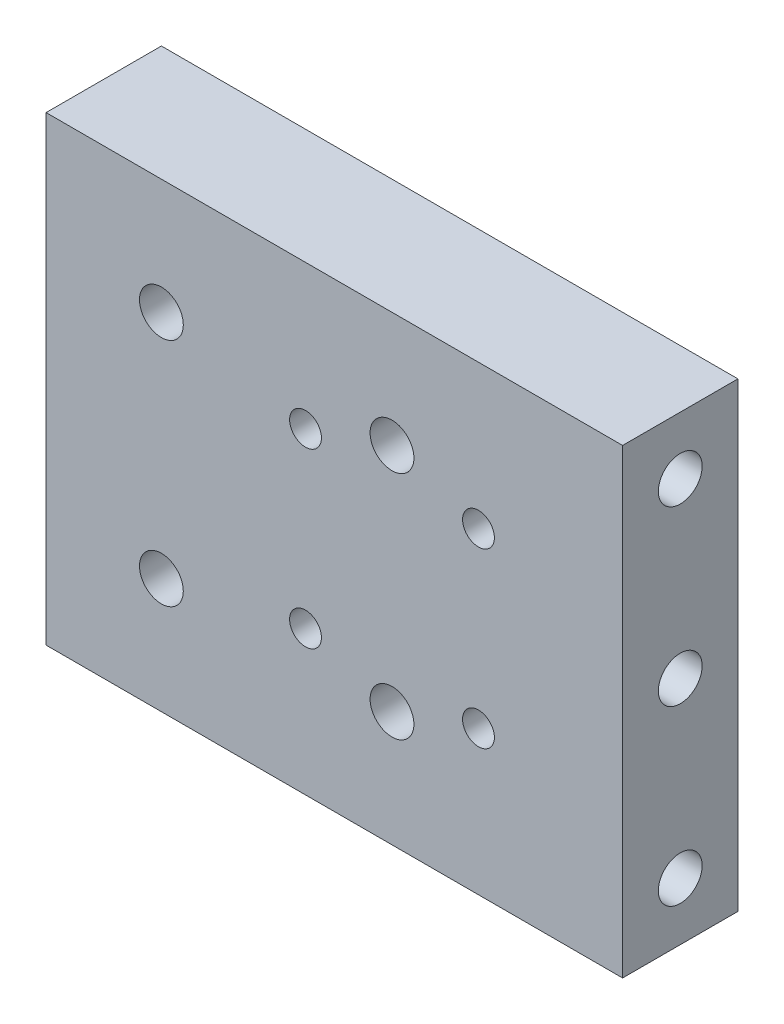
SolidWorks part; units mm, degrees
ref_plane "Front" through (0, 0, 0) normal (0, 0, 1) x (1, 0, 0)
ref_plane "Top" through (0, 0, 0) normal (0, 1, 0) x (1, 0, 0)
ref_plane "Right" through (0, 0, 0) normal (1, 0, 0) x (0, 0, -1)
sketch "Sketch1" plane through (0, 0, 0) normal (0, 0, 1) x (1, 0, 0)
  line L1 (0, 0) -> (-63.5, 0)
  line L2 (0, 0) -> (0, 50.8)
  line L3 (0, 50.8) -> (-63.5, 50.8)
  line L4 (-63.5, 0) -> (-63.5, 50.8)
  dimension "D1" = 63.5
  dimension "D2" = 50.8
extrude "Boss-Extrude1" add sketch "Sketch1" along normal mid plane 12.7
sketch "Sketch2" plane through (0, 0, 0) normal (1, 0, 0) x (0, 0, -1)
  line L0 (0, 50.8) -> (0, 0) construction
  line L3 (-6.35, 50.8) -> (6.35, 50.8) construction
  line L4 (-6.35, 0) -> (6.35, 0) construction
  point P6 (0, 44.45)
  point P8 (0, 25.4)
  point P9 (0, 6.35)
  dimension "D1" = 6.35
  dimension "D2" = 6.35
  dimension "D4" = 19.05
hole_wizard "#10-32 Threaded" positions "Sketch4" profile "Sketch5" hole size "#10" standard "ANSI Inch" end condition through all
sketch "Sketch4" plane through (0, 0, 0) normal (1, 0, 0) x (0, 0, -1)
  point P0 (0, 44.45)
  point P6 (0, 25.4)
  point P9 (0, 6.35)
sketch "Sketch5" plane through (0, 44.45, 0) normal (0, 1, 0) x (0, 0, -1)
  line L0 (0, 0) -> (0, 63.5)
  line L1 (0, 63.5) -> (2.413, 63.5)
  line L2 (2.413, 63.5) -> (2.413, 0)
  line L5 (2.413, 0) -> (0, 0)
  line L11 (0, -6.35) -> (0, 107.95) construction
  dimension "Thru Hole Dia." = 4.826
  dimension "Thru Hole Depth" = 63.5
hole_wizard "#10-32 Threaded Front" positions "Sketch7" profile "Sketch6" hole size "#10" standard "ANSI Inch" end condition through all
sketch "Sketch7" plane through (0, 0, 6.35) normal (0, 0, 1) x (1, 0, 0)
  line L0 (0, 50.8) -> (-63.5, 50.8) construction
  line L1 (-63.5, 50.8) -> (-63.5, 0) construction
  point P0 (-50.8, 38.1)
  point P2 (-25.4, 38.1)
  point P4 (-50.8, 12.7)
  point P6 (-25.4, 12.7)
  dimension "D1" = 25.4
  dimension "D2" = 25.4
  dimension "D3" = 12.7
  dimension "D4" = 12.7
sketch "Sketch6" plane through (-50.8, 38.1, 6.35) normal (1, 0, 0) x (0, -1, 0)
  line L0 (0, 0) -> (0, 12.7)
  line L1 (0, 12.7) -> (2.413, 12.7)
  line L2 (2.413, 12.7) -> (2.413, 0)
  line L5 (2.413, 0) -> (0, 0)
  line L11 (0, -6.35) -> (0, 107.95) construction
  dimension "Thru Hole Dia." = 4.826
  dimension "Thru Hole Depth" = 12.7
hole_wizard "#6-32 Threaded Front" positions "Sketch9" profile "Sketch8" hole size "#6" standard "ANSI Inch" end condition through all
sketch "Sketch9" plane through (0, 0, 6.35) normal (0, 0, 1) x (1, 0, 0)
  line L0 (0, 50.8) -> (-63.5, 50.8) construction
  line L1 (-63.5, 50.8) -> (-63.5, 0) construction
  point P0 (-34.925, 34.925)
  point P2 (-15.875, 34.925)
  point P4 (-15.875, 15.875)
  point P6 (-34.925, 15.875)
  dimension "D1" = 19.05
  dimension "D2" = 19.05
  dimension "D3" = 15.875
  dimension "D4" = 28.575
sketch "Sketch8" plane through (-34.925, 34.925, 6.35) normal (1, 0, 0) x (0, -1, 0)
  line L0 (0, 0) -> (0, 12.7)
  line L1 (0, 12.7) -> (1.7526, 12.7)
  line L2 (1.7526, 12.7) -> (1.7526, 0)
  line L5 (1.7526, 0) -> (0, 0)
  line L11 (0, -6.35) -> (0, 107.95) construction
  dimension "Thru Hole Dia." = 3.5052
  dimension "Thru Hole Depth" = 12.7
equation "\"D3@Sketch9\"=1.25/2"
